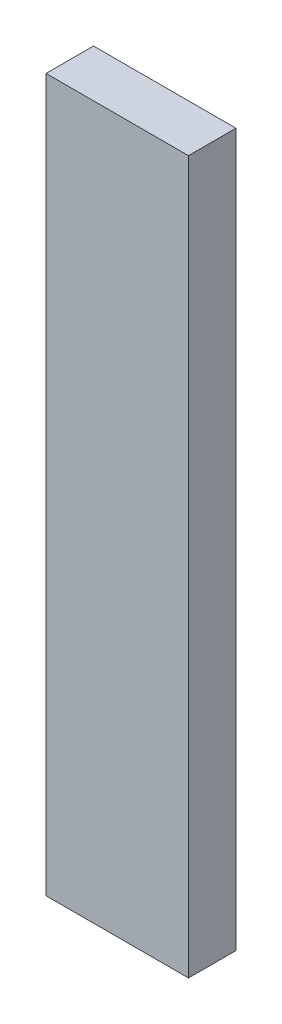
SolidWorks part; units mm, degrees
ref_plane "Plan de face" through (0, 0, 0) normal (0, 0, 1) x (1, 0, 0)
ref_plane "Plan de dessus" through (0, 0, 0) normal (0, 1, 0) x (1, 0, 0)
ref_plane "Plan de droite" through (0, 0, 0) normal (1, 0, 0) x (0, 0, -1)
sketch "Esquisse1" plane through (0, 0, 0) normal (0, 0, 1) x (1, 0, 0)
  line L0 (12.4356, -32.8768) -> (10.4053, -45.7963)
  line L1 (12.4356, -24.9395) -> (10.4053, -12.0201)
  line L2 (5.4659, -12.0201) -> (3.4356, -24.9395)
  line L3 (3.4356, -32.8768) -> (5.4659, -45.7963)
  line L5 (22.9356, -55.4082) -> (-7.0644, -55.4082)
  line L6 (22.9356, -55.4082) -> (22.9356, 94.5918)
  line L7 (22.9356, 94.5918) -> (-7.0644, 94.5918)
  line L8 (-7.0644, -55.4082) -> (-7.0644, 94.5918)
  arc A0 (12.4356, -24.9395) -> (12.4356, -32.8768) centre (7.9356, -28.9082) cw
  arc A1 (3.4356, -24.9395) -> (3.4356, -32.8768) centre (7.9356, -28.9082) ccw
  arc A2 (10.4053, -12.0201) -> (5.4659, -12.0201) centre (7.9356, -12.4082) ccw
  arc A3 (10.4053, -45.7963) -> (5.4659, -45.7963) centre (7.9356, -45.4082) cw
  dimension "D1" = 2.5
  dimension "D7" = 2.5
  dimension "D13" = 6
  dimension "D14" = 6
  dimension "D15" = 10
  dimension "D16" = 15
  dimension "D17" = 15
  dimension "D2" = 13.078
  dimension "D3" = 13.078
  dimension "D4" = 17.862
  dimension "D5" = 16.5
  dimension "D6" = 16.5
  dimension "D8" = 17.862
  dimension "D9" = 13.078
  dimension "D10" = 13.078
  dimension "D11" = 16.5
  dimension "D12" = 16.5
  dimension "D18" = 150
extrude "Boss.-Extru.1" add sketch "Esquisse1" along normal blind 5
sketch "Esquisse2" plane through (0, 0, 5) normal (0, 0, 1) x (1, 0, 0)
  line L1 (-7.0644, 94.5918) -> (22.9356, 94.5918)
  line L2 (-7.0644, 94.5918) -> (-7.0644, -55.4082)
  line L3 (-7.0644, -55.4082) -> (22.9356, -55.4082)
  line L4 (22.9356, 94.5918) -> (22.9356, -55.4082)
extrude "Boss.-Extru.2" add sketch "Esquisse2" along normal blind 5
